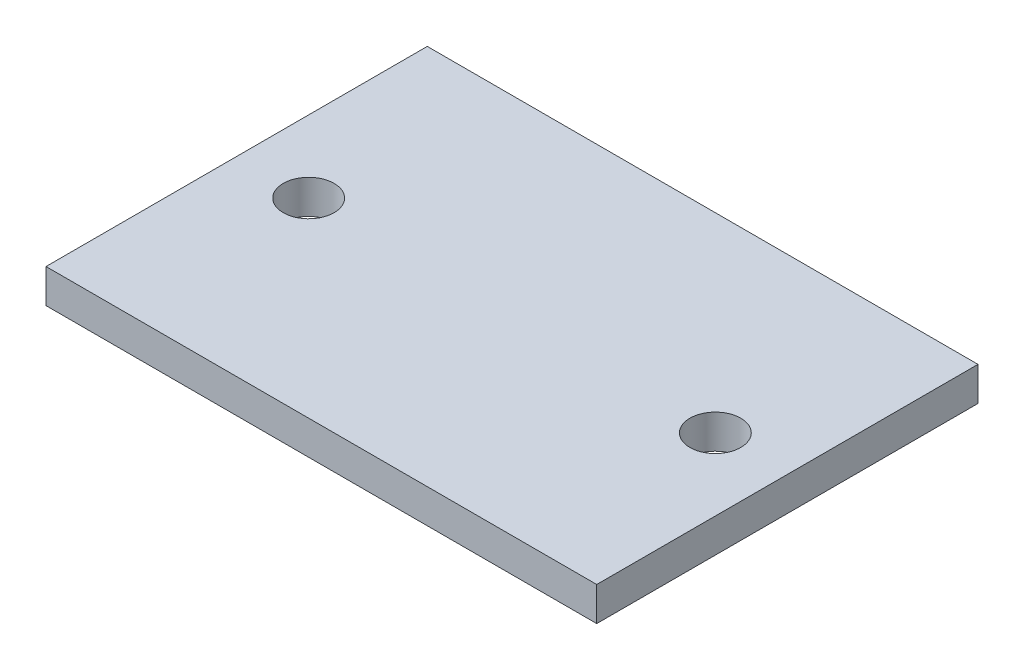
SolidWorks part; units mm, degrees
ref_plane "Front Plane" through (0, 0, 0) normal (0, 0, 1) x (1, 0, 0)
ref_plane "Top Plane" through (0, 0, 0) normal (0, 1, 0) x (1, 0, 0)
ref_plane "Right Plane" through (0, 0, 0) normal (1, 0, 0) x (0, 0, -1)
sketch "Sketch1" plane through (0, 0, 0) normal (0, 1, 0) x (1, 0, 0)
  line L1 (32.5, -22.5) -> (-32.5, -22.5)
  line L2 (32.5, -22.5) -> (32.5, 22.5)
  line L3 (32.5, 22.5) -> (-32.5, 22.5)
  line L4 (-32.5, -22.5) -> (-32.5, 22.5)
  line L5 (32.5, -22.5) -> (-32.5, 22.5) construction
  line L6 (32.5, 22.5) -> (-32.5, -22.5) construction
  point P0 (0, 0)
  dimension "D1" = 65
  dimension "D2" = 45
extrude "Boss-Extrude1" add sketch "Sketch1" along normal blind 4
sketch "Sketch2" plane through (0, 4, 0) normal (0, 1, 0) x (1, 0, 0)
  circle A0 centre (0, 0) radius 24 construction
  circle A1 centre (-24, 0) radius 3
  circle A2 centre (24, 0) radius 3
  dimension "D1" = 48
  dimension "D2" = 6
extrude "Cut-Extrude1" cut sketch "Sketch2" against normal through all both and the other way through all
